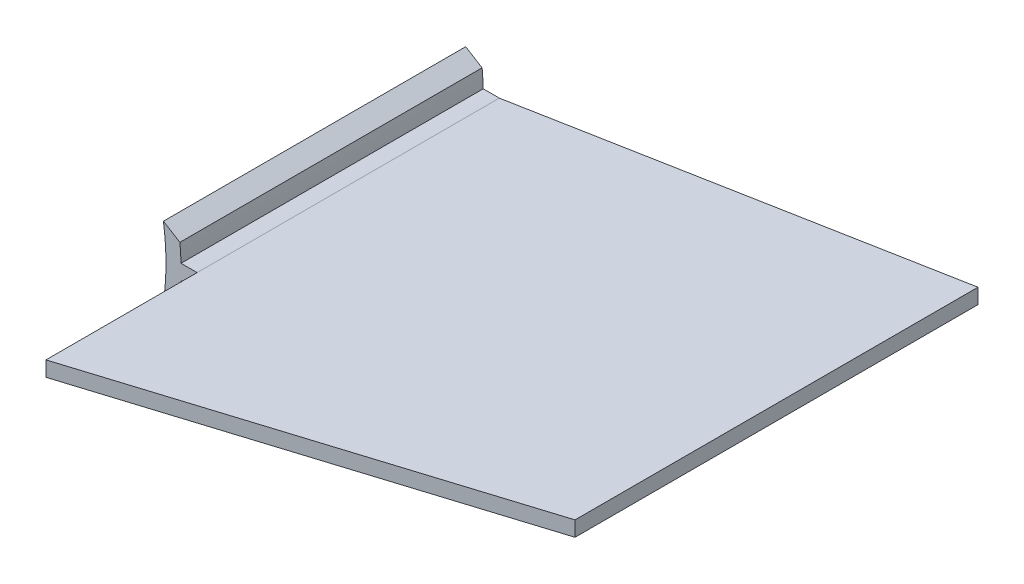
SolidWorks part; units mm, degrees
ref_plane "前视基准面" through (0, 0, 0) normal (0, 0, 1) x (1, 0, 0)
ref_plane "上视基准面" through (0, 0, 0) normal (0, 1, 0) x (1, 0, 0)
ref_plane "右视基准面" through (0, 0, 0) normal (1, 0, 0) x (0, 0, -1)
other "Configuration Table"
sketch "草图1" plane through (0, 0, 0) normal (0, 0, 1) x (1, 0, 0)
  circle A1 centre (0, 0) radius 55
  dimension "D1" = 110
extrude "凸台-拉伸1" add sketch "草图1" along normal blind 190
sketch "草图2" plane through (0, 0, 190) normal (0, 0, 1) x (1, 0, 0)
  circle A0 centre (0, 0) radius 51.8
  dimension "D1" = 103.6
extrude "切除-拉伸1" cut sketch "草图2" against normal blind 186.8
sketch "草图3" plane through (0, 0, 0) normal (0, 0, -1) x (-1, 0, 0)
  circle A0 centre (0, 0) radius 15
  dimension "D1" = 30
extrude "切除-拉伸2" cut sketch "草图3" against normal blind 10
sketch "草图4" plane through (0, 0, 3.2) normal (0, 0, 1) x (1, 0, 0)
  circle A0 centre (0, 0) radius 15
  circle A1 centre (0, 0) radius 18.2
  dimension "D1" = 36.4
extrude "凸台-拉伸2" add sketch "草图4" along normal blind 188
sketch "草图5" plane through (0, 0, 190) normal (0, 0, 1) x (1, 0, 0)
  circle A0 centre (0, 0) radius 55
extrude "凸台-拉伸5" add sketch "草图5" along normal blind 3.2
sketch "草图6" plane through (0, 0, 193.2) normal (0, 0, 1) x (1, 0, 0)
  line L0 (0, 0) -> (-55, 0)
  line L1 (0, 0) -> (27.5, 47.6314)
  line L2 (0, 0) -> (27.5, -47.6314)
  circle A0 centre (0, 0) radius 55 construction
  point P10 (0, 0)
  dimension "D1" = 3
ref_plane "基准面1" through (0, 0, 0) normal (0, 1, 0) x (-1, 0, 0)
sketch "草图8" plane through (0, 0, 0) normal (0, 1, 0) x (-1, 0, 0)
  line L0 (-55, 90) -> (-135, 65)
  line L1 (-55, 193.2) -> (-55, 0) construction
  line L2 (-135, 65) -> (-135, -15)
  line L3 (-135, -15) -> (-55, 0)
  line L5 (-55, 90) -> (-53, 90)
  line L6 (-53, 90) -> (-53, 0)
  line L7 (-55, 0) -> (55, 0) construction
  line L8 (-53, 0) -> (-55, 0)
  dimension "D1" = 65
  dimension "D2" = 25
  dimension "D3" = 80
  dimension "D4" = 2
  dimension "D5" = 80
extrude "凸台-拉伸6" add sketch "草图8" along normal mid plane 3
sketch "草图9" plane through (0, 0, 193.2) normal (0, 0, 1) x (1, 0, 0)
  line L0 (24.3395, -49.3213) -> (24.3395, -150.1593)
  line L1 (-116.2439, 159.5316) -> (24.3395, 159.5316)
  line L2 (-116.2439, 159.5316) -> (-116.2439, -150.1593)
  line L3 (-116.2439, -150.1593) -> (24.3395, -150.1593)
  line L4 (24.3395, 159.5316) -> (24.3395, 49.3213)
  arc A0 (24.3395, -49.3213) -> (24.3395, 49.3213) centre (0, 0) ccw
extrude "切除-拉伸3" cut sketch "草图9" against normal blind 300
ref_plane "基准面2" through (55, 0, 0) normal (0, 0, 1) x (1, 0, 0)
sketch "草图10" plane through (55, 0, 0) normal (0, 0, 1) x (1, 0, 0)
  line L0 (0, 0) -> (-55, 0) construction
  line L1 (-3.2217, 1.5) -> (-0.0205, 1.5)
  line L3 (-3.4419, 5) -> (-6.7047, 7)
  line L4 (-3.4419, -5) -> (-6.7047, -7)
  line L7 (-3.2217, -1.5) -> (-0.0205, -1.5)
  arc A2 (-6.7047, -7) -> (-6.7047, 7) centre (-55, 0) ccw
  arc A3 (-3.2217, 1.5) -> (-3.4419, 5) centre (-55, 0) ccw
  arc A4 (-3.2217, -1.5) -> (-3.4419, -5) centre (-55, 0) cw
  arc A5 (-0.0205, -1.5) -> (-0.0205, 1.5) centre (-55, 0) ccw
  dimension "D2" = 51.8
  dimension "D3" = 97.6
  dimension "D4" = 5
  dimension "D5" = 7
extrude "凸台-拉伸7" add sketch "草图10" along normal blind 60 separate body
equation "\"3。2\"=1"
